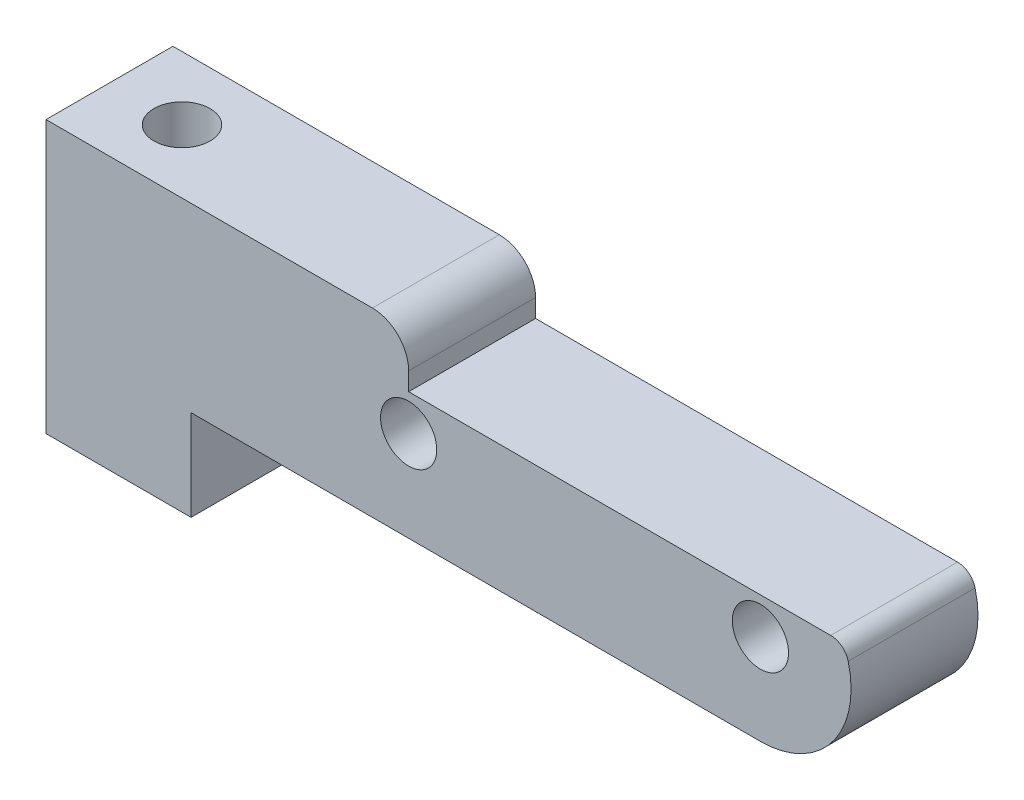
SolidWorks part; units mm, degrees
ref_plane "Alzado" through (0, 0, 0) normal (0, 0, 1) x (1, 0, 0)
ref_plane "Planta" through (0, 0, 0) normal (0, 1, 0) x (1, 0, 0)
ref_plane "Vista lateral" through (0, 0, 0) normal (1, 0, 0) x (0, 0, -1)
sketch "Croquis1" plane through (0, 0, 0) normal (0, 0, 1) x (1, 0, 0)
  line L0 (-9.7, 0) -> (9.7, 0) construction
  line L1 (-9.7, 0) -> (9.7, 0) construction
  line L2 (-9.7, 5) -> (9.7, 5)
  line L3 (-9.7, -5) -> (9.7, -5)
  line L4 (-14.2826, 2) -> (14.2826, 2)
  line L5 (-9.7, -5) -> (-29.7, -5)
  line L6 (-29.7, -5) -> (-29.7, 5)
  line L7 (-9.7, 5) -> (-29.7, 5)
  line L8 (-9.7, 5) -> (-9.7, 2)
  circle A0 centre (-9.7, 0) radius 1.55
  circle A1 centre (9.7, 0) radius 1.55
  arc A2 (-9.7, 5) -> (-9.7, -5) centre (-9.7, 0) ccw
  arc A3 (9.7, -5) -> (9.7, 5) centre (9.7, 0) ccw
  point P4 (0, 0)
  point P5 (0, 0)
  dimension "D2" = 3.1
  dimension "D1" = 19.4
  dimension "D3" = 10
  dimension "D4" = 7
  dimension "D5" = 20
extrude "Saliente-Extruir1" add sketch "Croquis1" along normal blind 7 contours A2 L7 L6 L5 | L3 A3 L4 A2 A0 A1 | L8 A2 L4
fillet "Redondeo1" radius 1 1 edges at (14.2826, 2, 3.5)
fillet "Redondeo2" radius 2 1 edges at (-9.7, 5, 3.5)
sketch "Croquis2" plane through (0, 5, 0) normal (0, 1, 0) x (1, 0, 0)
  line L0 (-29.7, -7) -> (-29.7, 0) construction
  circle A0 centre (-25.7, -3.5) radius 1.55
  point P4 (-29.7, -3.5)
  dimension "D1" = 3.1
  dimension "D2" = 4
extrude "Cortar-Extruir1" cut sketch "Croquis2" against normal through all
sketch "Croquis3" plane through (0, -5, 0) normal (0, -1, 0) x (1, 0, 0)
  line L0 (-29.7, 7) -> (-29.7, 0) construction
  line L1 (-29.7, 7) -> (-21.7, 7)
  line L2 (-29.7, 7) -> (-29.7, 0)
  line L3 (-29.7, 0) -> (-21.7, 0)
  line L4 (-21.7, 7) -> (-21.7, 0)
  line L5 (-29.7, 7) -> (-21.7, 0) construction
  line L6 (-29.7, 0) -> (-21.7, 7) construction
  line L7 (9.7, 7) -> (-29.7, 7) construction
  circle A0 centre (-25.7, 3.5) radius 1.55 construction
  circle A1 centre (-25.7, 3.5) radius 1.55
  point P0 (-25.7, 3.5)
extrude "Saliente-Extruir2" add sketch "Croquis3" along normal blind 5
